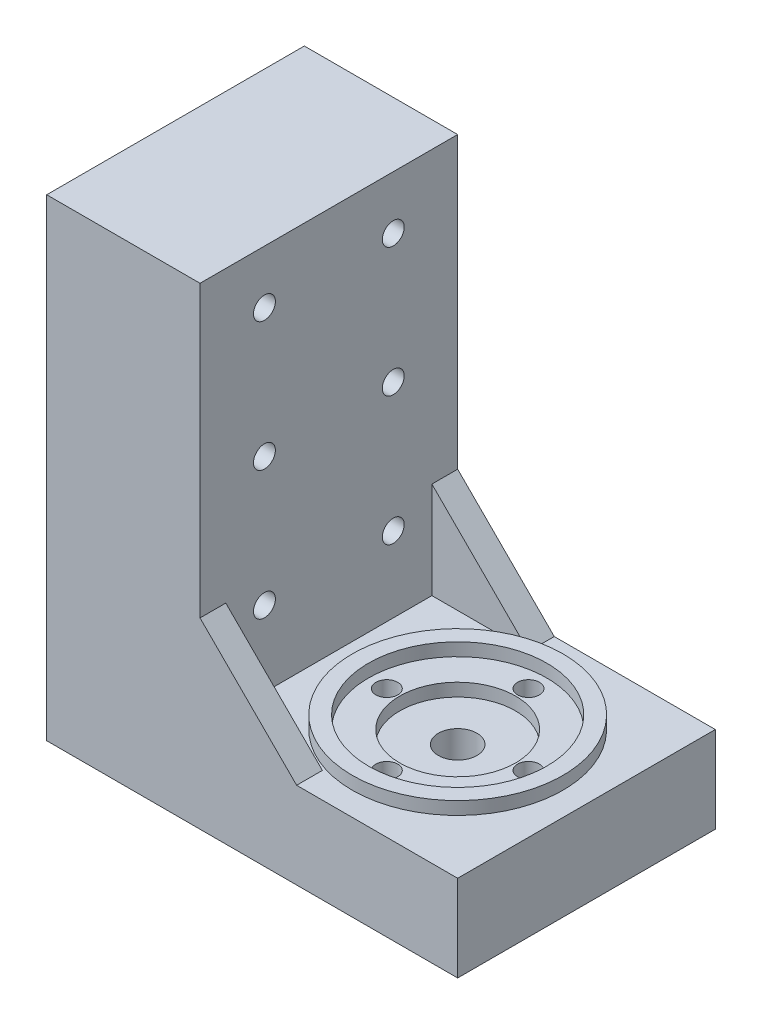
SolidWorks part; units mm, degrees
ref_plane "Front Plane" through (0, 0, 0) normal (0, 0, 1) x (1, 0, 0)
ref_plane "Top Plane" through (0, 0, 0) normal (0, 1, 0) x (1, 0, 0)
ref_plane "Right Plane" through (0, 0, 0) normal (1, 0, 0) x (0, 0, -1)
sketch "Sketch1" plane through (0, 0, 0) normal (0, 1, 0) x (1, 0, 0)
  line L1 (0, 0) -> (40, 0)
  line L2 (0, 0) -> (0, 40)
  line L3 (0, 40) -> (40, 40)
  line L4 (40, 0) -> (40, 40)
  dimension "D1" = 40
  dimension "D2" = 40
extrude "Boss-Extrude1" add sketch "Sketch1" along normal blind 13.4135 contours L3 L4 L1 L2
sketch "Sketch2" plane through (0, 13.4135, 0) normal (0, 1, 0) x (1, 0, 0)
  line L0 (0, 40) -> (40, 0) construction
  line L1 (40, 40) -> (0, 0) construction
  circle A0 centre (20, 20) radius 3
  dimension "D1" = 6
extrude "Cut-Extrude1" cut sketch "Sketch2" against normal through all
sketch "Sketch3" plane through (0, 0, 0) normal (-1, 0, 0) x (0, 0, 1)
  line L1 (-40, 0) -> (0, 0)
  line L2 (-40, 0) -> (-40, 73.4135)
  line L3 (-40, 73.4135) -> (0, 73.4135)
  line L4 (0, 0) -> (0, 73.4135)
  dimension "D1" = 73.4135
extrude "Boss-Extrude2" add sketch "Sketch3" along normal blind 23.8042
sketch "Sketch4" plane through (0, 0, 0) normal (1, 0, 0) x (0, 0, -1)
  line L0 (0, 13.4135) -> (0, 73.4135) construction
  circle A0 centre (10, 65.1313) radius 1.7
  circle A1 centre (30, 65.1313) radius 1.7
  circle A2 centre (10, 45.1313) radius 1.7
  circle A3 centre (30, 45.1313) radius 1.7
  circle A4 centre (10, 25.1313) radius 1.7
  circle A5 centre (30, 25.1313) radius 1.7
  dimension "D5" = 3.4
  dimension "D1" = 10
  dimension "D2" = 20
  dimension "D3" = 20
  dimension "D4" = 20
extrude "Cut-Extrude2" cut sketch "Sketch4" against normal through all
sketch "Sketch5" plane through (0, 13.4135, 0) normal (0, 1, 0) x (1, 0, 0)
  line L0 (0, 40) -> (40, 0) construction
  line L1 (0, 0) -> (40, 40) construction
  circle A0 centre (20, 20) radius 11
  circle A1 centre (20, 31) radius 1.7
  circle A2 centre (31, 20) radius 1.7
  circle A3 centre (20, 9) radius 1.7
  circle A4 centre (9, 20) radius 1.7
  dimension "D1" = 22
  dimension "D2" = 3.4
extrude "Cut-Extrude3" cut sketch "Sketch5" against normal through all contours A2 | A1 | A3 | A4
sketch "Sketch6" plane through (0, 13.4135, 0) normal (0, 1, 0) x (1, 0, 0)
  circle A0 centre (20, 20) radius 13.85
  circle A1 centre (20, 20) radius 16.35
  dimension "D1" = 27.7
  dimension "D2" = 32.7
extrude "Boss-Extrude3" add sketch "Sketch6" along normal blind 2 contours A1 | A0
sketch "Sketch7" plane through (0, 0, -40) normal (0, 0, -1) x (-1, 0, 0)
  line L0 (-15, 13.4135) -> (0, 28.4135)
  line L1 (0, 13.4135) -> (-40, 13.4135) construction
  line L2 (0, 73.4135) -> (0, 13.4135) construction
  line L3 (0, 28.4135) -> (0, 13.4135)
  line L4 (0, 13.4135) -> (-15, 13.4135)
  dimension "D1" = 15
  dimension "D2" = 15
extrude "Boss-Extrude4" add sketch "Sketch7" against normal blind 4
sketch "Sketch8" plane through (0, 0, 0) normal (0, 0, 1) x (1, 0, 0)
  line L0 (0, 28.4135) -> (0, 13.4135)
  line L1 (0, 28.4135) -> (15, 13.4135)
  line L2 (0, 13.4135) -> (40, 13.4135) construction
  line L3 (0, 28.4135) -> (15, 13.4135) construction
  line L4 (15, 13.4135) -> (0, 13.4135)
extrude "Boss-Extrude5" add sketch "Sketch8" against normal blind 4
sketch "Sketch9" plane through (0, 13.4135, 0) normal (0, 1, 0) x (1, 0, 0)
  circle A0 centre (20, 20) radius 9
  dimension "D1" = 18
extrude "Cut-Extrude4" cut sketch "Sketch9" against normal blind 2
equation "\"b\"= 40mm'F1 Width (mm)"
equation "\"L_1\"= 40mm'F1 Length (mm)"
equation "\"P\"= 300'Load (Newtons)"
equation "\"SF\"= 3'Safety Factor (Unitless)"
equation "\"Delta_max\"= 0.30mm'Max Deflection (mm)"
equation "\"L_S\"= 18mm'Motor Shaft Length"
equation "\"E\"= 1790'Youngs Mod (MPa)"
equation "\"Sigma_y\"= 29.6'Yield Strength (MPa)"
equation "\"D1@Sketch1\"=\"b\""
equation "\"M\"= ( \"P\" ) * ( \"L_S\" )'Moment (N*mm)"
equation "\"D2@Sketch1\"= \"L_1\""
equation "\"h_1\"= ( ( 2 * \"SF\" * \"M\" * ( \"L_1\" ) ^ 2 ) / ( \"E\" * \"Delta_max\" * \"b\" ) ) ^ ( 1 / 3 )'F1 Thickness (mm)"
equation "\"D1@Boss-Extrude1\"=\"h_1\""
equation "\"D_S\"= 6mm'Motor Shaft Diameter (mm)"
equation "\"D1@Sketch2\"=\"D_S\""
equation "\"L_2\"= 60mm'F2 Length (Fixed)"
equation "\"L_Total\"= \"L_2\" + \"h_1\"'F2 Length (Fixed + Free)"
equation "\"h_2\"= ( ( ( \"h_1\" / 2 ) * ( \"P\" ) * ( \"L_1\" ) * ( \"L_2\" ^ 2 ) ) / ( ( \"E\" ) * ( \"b\" ) * ( \"Delta_max\" ) ) ) ^ ( 1 / 3 )'F2 Thickness (mm)"
equation "\"D1@Boss-Extrude2\"=\"h_2\""
equation "\"D1@Sketch3\"=\"L_Total\""
